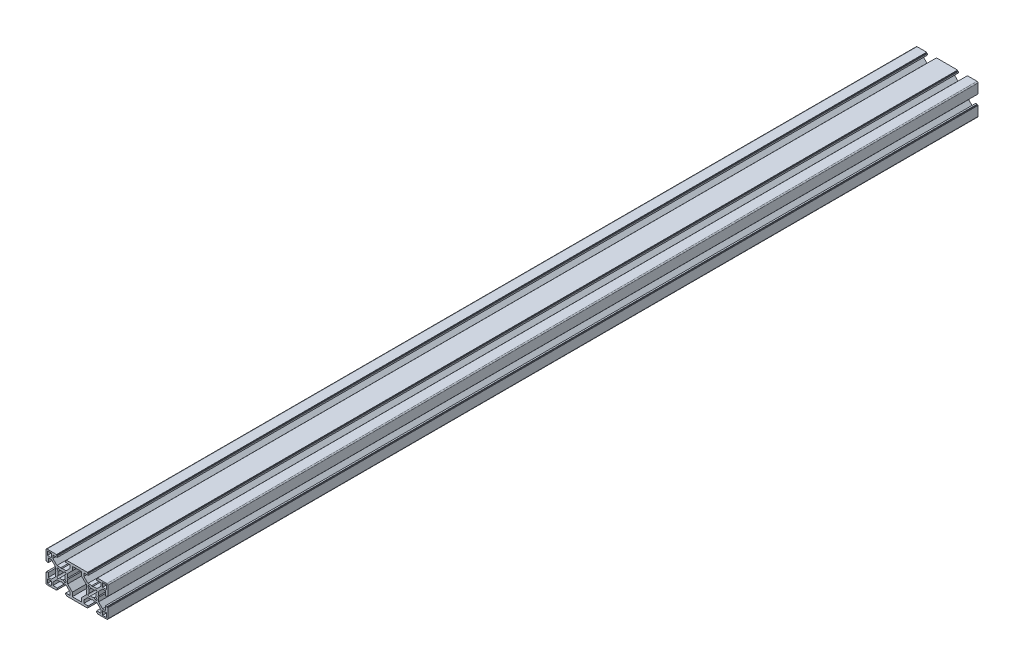
SolidWorks part; units mm, degrees
material "6061 Alloy"
ref_plane "Front Plane" through (0, 0, 0) normal (0, 0, 1) x (1, 0, 0)
ref_plane "Top Plane" through (0, 0, 0) normal (0, 1, 0) x (1, 0, 0)
ref_plane "Right Plane" through (0, 0, 0) normal (1, 0, 0) x (0, 0, -1)
sketch3d "3DSketch1"
  line L0 (0, 0, 0) -> (0, 0, -843)
  dimension "D1" = 843
other "T-slot CNCCAT-3060(1)"
ref_plane "Plane1" through (0, 0, 0) normal (0, 0, -1) x (1, 0, 0)
sketch "Sketch22" plane through (0, 0, 0) normal (0, 0, -1) x (1, 0, 0)
  line L0 (-15, 0) -> (15, 0) construction
  line L1 (30, 15) -> (-30, 15) construction
  line L2 (30, 15) -> (30, -15) construction
  line L3 (24.7696, 13.7304) -> (24.7696, 9.7696)
  line L4 (28.7304, 13.7304) -> (24.7696, 13.7304)
  line L5 (28.7304, 9.7696) -> (28.7304, 13.7304)
  line L6 (24.7696, 9.7696) -> (28.7304, 9.7696)
  line L7 (19.1095, -2.6952) -> (18.0788, -1.6646)
  line L8 (16.6646, -3.0788) -> (17.6952, -4.1095)
  line L9 (-4.492, -12.8) -> (4.492, -12.8)
  line L10 (-4.492, -8.9524) -> (-4.492, -12.8)
  line L11 (-9.0433, -4.4011) -> (-4.492, -8.9524)
  line L12 (-9.0433, -0.6196) -> (-9.0433, -4.4011)
  line L13 (-9.6629, 0) -> (-9.0433, -0.6196)
  line L14 (-9.0433, 0.6196) -> (-9.6629, 0)
  line L15 (-9.0433, 4.4011) -> (-9.0433, 0.6196)
  line L16 (-4.492, 8.9524) -> (-9.0433, 4.4011)
  line L17 (-4.492, 12.8) -> (-4.492, 8.9524)
  line L18 (4.492, 12.8) -> (-4.492, 12.8)
  line L19 (4.492, 8.9524) -> (4.492, 12.8)
  line L20 (9.0433, 4.4011) -> (4.492, 8.9524)
  line L21 (9.0433, 0.6196) -> (9.0433, 4.4011)
  line L22 (9.6629, 0) -> (9.0433, 0.6196)
  line L23 (9.0433, -0.6196) -> (9.6629, 0)
  line L24 (9.0433, -4.4011) -> (9.0433, -0.6196)
  line L25 (4.492, -8.9524) -> (9.0433, -4.4011)
  line L26 (4.492, -12.8) -> (4.492, -8.9524)
  line L27 (12.3048, -4.1095) -> (13.3354, -3.0788)
  line L28 (11.9212, -1.6646) -> (10.8905, -2.6952)
  line L29 (10.8905, 2.6952) -> (11.9212, 1.6646)
  line L30 (13.3354, 3.0788) -> (12.3048, 4.1095)
  line L31 (17.6952, 4.1095) -> (16.6646, 3.0788)
  line L32 (18.0788, 1.6646) -> (19.1095, 2.6952)
  line L33 (28.7304, -13.7304) -> (28.7304, -9.7696)
  line L34 (24.7696, -13.7304) -> (28.7304, -13.7304)
  line L35 (24.7696, -9.7696) -> (24.7696, -13.7304)
  line L36 (28.7304, -9.7696) -> (24.7696, -9.7696)
  line L37 (-28.7304, 13.7304) -> (-28.7304, 9.7696)
  line L38 (-24.7696, 13.7304) -> (-28.7304, 13.7304)
  line L39 (-24.7696, 9.7696) -> (-24.7696, 13.7304)
  line L40 (-28.7304, 9.7696) -> (-24.7696, 9.7696)
  line L41 (-19.1095, 2.6952) -> (-18.0788, 1.6646)
  line L42 (-16.6646, 3.0788) -> (-17.6952, 4.1095)
  line L43 (-12.3048, 4.1095) -> (-13.3354, 3.0788)
  line L44 (-11.9212, 1.6646) -> (-10.8905, 2.6952)
  line L45 (-10.8905, -2.6952) -> (-11.9212, -1.6646)
  line L46 (-13.3354, -3.0788) -> (-12.3048, -4.1095)
  line L47 (-17.6952, -4.1095) -> (-16.6646, -3.0788)
  line L48 (-18.0788, -1.6646) -> (-19.1095, -2.6952)
  line L49 (-24.7696, -13.7304) -> (-24.7696, -9.7696)
  line L50 (-28.7304, -13.7304) -> (-24.7696, -13.7304)
  line L51 (-28.7304, -9.7696) -> (-28.7304, -13.7304)
  line L52 (-24.7696, -9.7696) -> (-28.7304, -9.7696)
  line L53 (30, -15) -> (-30, -15) construction
  line L54 (-30, 15) -> (-30, -15) construction
  line L55 (30, 15) -> (-30, -15) construction
  line L56 (30, -15) -> (-30, 15) construction
  line L57 (-20.3371, 0) -> (-20.9567, -0.6196)
  line L58 (-20.9567, -0.6196) -> (-20.9567, -4.4011)
  line L59 (-20.9567, -4.4011) -> (-24.8637, -8.308)
  line L60 (-24.8637, -8.308) -> (-27.8, -8.308)
  line L61 (-27.8, -8.308) -> (-27.8, -4.1)
  line L62 (-27.8, -4.1) -> (-29.2339, -4.1)
  line L63 (-29.2339, -4.1) -> (-29.2339, -4.7563)
  line L64 (-29.2339, -4.7563) -> (-30, -4.7563)
  line L65 (-30, -4.7563) -> (-30, -14)
  line L66 (-29, -15) -> (-19.7563, -15)
  line L67 (-19.7563, -15) -> (-19.7563, -14.2339)
  line L68 (-19.7563, -14.2339) -> (-19.1, -14.2339)
  line L69 (-19.1, -14.2339) -> (-19.1, -12.8)
  line L70 (-19.1, -12.8) -> (-23.308, -12.8)
  line L71 (-23.308, -12.8) -> (-23.308, -9.8637)
  line L72 (-23.308, -9.8637) -> (-19.4011, -5.9567)
  line L73 (-19.4011, -5.9567) -> (-15.6196, -5.9567)
  line L74 (-15.6196, -5.9567) -> (-15, -5.3371)
  line L75 (-15, -5.3371) -> (-14.3804, -5.9567)
  line L76 (-14.3804, -5.9567) -> (-10.5989, -5.9567)
  line L77 (-10.5989, -5.9567) -> (-6.692, -9.8637)
  line L78 (-6.692, -9.8637) -> (-6.692, -12.8)
  line L79 (-6.692, -12.8) -> (-10.9, -12.8)
  line L80 (-10.9, -12.8) -> (-10.9, -14.2339)
  line L81 (-10.9, -14.2339) -> (-10.2437, -14.2339)
  line L82 (-10.2437, -14.2339) -> (-10.2437, -15)
  line L83 (-10.2437, -15) -> (10.2437, -15)
  line L84 (10.2437, -15) -> (10.2437, -14.2339)
  line L85 (10.2437, -14.2339) -> (10.9, -14.2339)
  line L86 (10.9, -14.2339) -> (10.9, -12.8)
  line L87 (10.9, -12.8) -> (6.692, -12.8)
  line L88 (6.692, -12.8) -> (6.692, -9.8637)
  line L89 (6.692, -9.8637) -> (10.5989, -5.9567)
  line L90 (10.5989, -5.9567) -> (14.3804, -5.9567)
  line L91 (14.3804, -5.9567) -> (15, -5.3371)
  line L92 (15, -5.3371) -> (15.6196, -5.9567)
  line L93 (15.6196, -5.9567) -> (19.4011, -5.9567)
  line L94 (19.4011, -5.9567) -> (23.308, -9.8637)
  line L95 (23.308, -9.8637) -> (23.308, -12.8)
  line L96 (23.308, -12.8) -> (19.1, -12.8)
  line L97 (19.1, -12.8) -> (19.1, -14.2339)
  line L98 (19.1, -14.2339) -> (19.7563, -14.2339)
  line L99 (19.7563, -14.2339) -> (19.7563, -15)
  line L100 (19.7563, -15) -> (29, -15)
  line L101 (30, -14) -> (30, -4.7563)
  line L102 (30, -4.7563) -> (29.2339, -4.7563)
  line L103 (29.2339, -4.7563) -> (29.2339, -4.1)
  line L104 (29.2339, -4.1) -> (27.8, -4.1)
  line L105 (27.8, -4.1) -> (27.8, -8.308)
  line L106 (27.8, -8.308) -> (24.8637, -8.308)
  line L107 (24.8637, -8.308) -> (20.9567, -4.4011)
  line L108 (20.9567, -4.4011) -> (20.9567, -0.6196)
  line L109 (20.9567, -0.6196) -> (20.3371, 0)
  line L110 (20.3371, 0) -> (20.9567, 0.6196)
  line L111 (20.9567, 0.6196) -> (20.9567, 4.4011)
  line L112 (20.9567, 4.4011) -> (24.8637, 8.308)
  line L113 (24.8637, 8.308) -> (27.8, 8.308)
  line L114 (27.8, 8.308) -> (27.8, 4.1)
  line L115 (27.8, 4.1) -> (29.2339, 4.1)
  line L116 (29.2339, 4.1) -> (29.2339, 4.7563)
  line L117 (29.2339, 4.7563) -> (30, 4.7563)
  line L118 (30, 4.7563) -> (30, 14)
  line L119 (29, 15) -> (19.7563, 15)
  line L120 (19.7563, 15) -> (19.7563, 14.2339)
  line L121 (19.7563, 14.2339) -> (19.1, 14.2339)
  line L122 (19.1, 14.2339) -> (19.1, 12.8)
  line L123 (19.1, 12.8) -> (23.308, 12.8)
  line L124 (23.308, 12.8) -> (23.308, 9.8637)
  line L125 (23.308, 9.8637) -> (19.4011, 5.9567)
  line L126 (19.4011, 5.9567) -> (15.6196, 5.9567)
  line L127 (15.6196, 5.9567) -> (15, 5.3371)
  line L128 (15, 5.3371) -> (14.3804, 5.9567)
  line L129 (14.3804, 5.9567) -> (10.5989, 5.9567)
  line L130 (10.5989, 5.9567) -> (6.692, 9.8637)
  line L131 (6.692, 9.8637) -> (6.692, 12.8)
  line L132 (6.692, 12.8) -> (10.9, 12.8)
  line L133 (10.9, 12.8) -> (10.9, 14.2339)
  line L134 (10.9, 14.2339) -> (10.2437, 14.2339)
  line L135 (10.2437, 14.2339) -> (10.2437, 15)
  line L136 (10.2437, 15) -> (-10.2437, 15)
  line L137 (-10.2437, 15) -> (-10.2437, 14.2339)
  line L138 (-10.2437, 14.2339) -> (-10.9, 14.2339)
  line L139 (-10.9, 14.2339) -> (-10.9, 12.8)
  line L140 (-10.9, 12.8) -> (-6.692, 12.8)
  line L141 (-6.692, 12.8) -> (-6.692, 9.8637)
  line L142 (-6.692, 9.8637) -> (-10.5989, 5.9567)
  line L143 (-10.5989, 5.9567) -> (-14.3804, 5.9567)
  line L144 (-14.3804, 5.9567) -> (-15, 5.3371)
  line L145 (-15, 5.3371) -> (-15.6196, 5.9567)
  line L146 (-15.6196, 5.9567) -> (-19.4011, 5.9567)
  line L147 (-19.4011, 5.9567) -> (-23.308, 9.8637)
  line L148 (-23.308, 9.8637) -> (-23.308, 12.8)
  line L149 (-23.308, 12.8) -> (-19.1, 12.8)
  line L150 (-19.1, 12.8) -> (-19.1, 14.2339)
  line L151 (-19.1, 14.2339) -> (-19.7563, 14.2339)
  line L152 (-19.7563, 14.2339) -> (-19.7563, 15)
  line L153 (-19.7563, 15) -> (-29, 15)
  line L154 (-30, 14) -> (-30, 4.7563)
  line L155 (-30, 4.7563) -> (-29.2339, 4.7563)
  line L156 (-29.2339, 4.7563) -> (-29.2339, 4.1)
  line L157 (-29.2339, 4.1) -> (-27.8, 4.1)
  line L158 (-27.8, 4.1) -> (-27.8, 8.308)
  line L159 (-27.8, 8.308) -> (-24.8637, 8.308)
  line L160 (-24.8637, 8.308) -> (-20.9567, 4.4011)
  line L161 (-20.9567, 4.4011) -> (-20.9567, 0.6196)
  line L162 (-20.9567, 0.6196) -> (-20.3371, 0)
  arc A0 (17.6952, -4.1095) -> (19.1095, -2.6952) centre (18.4023, -3.4023) ccw
  arc A1 (13.3354, -3.0788) -> (16.6646, -3.0788) centre (15, 0) ccw
  arc A2 (10.8905, -2.6952) -> (12.3048, -4.1095) centre (11.5977, -3.4023) ccw
  arc A3 (11.9212, 1.6646) -> (11.9212, -1.6646) centre (15, 0) ccw
  arc A4 (12.3048, 4.1095) -> (10.8905, 2.6952) centre (11.5977, 3.4023) ccw
  arc A5 (16.6646, 3.0788) -> (13.3354, 3.0788) centre (15, 0) ccw
  arc A6 (19.1095, 2.6952) -> (17.6952, 4.1095) centre (18.4023, 3.4023) ccw
  arc A7 (18.0788, -1.6646) -> (18.0788, 1.6646) centre (15, 0) ccw
  arc A8 (-17.6952, 4.1095) -> (-19.1095, 2.6952) centre (-18.4023, 3.4023) ccw
  arc A9 (-13.3354, 3.0788) -> (-16.6646, 3.0788) centre (-15, 0) ccw
  arc A10 (-10.8905, 2.6952) -> (-12.3048, 4.1095) centre (-11.5977, 3.4023) ccw
  arc A11 (-11.9212, -1.6646) -> (-11.9212, 1.6646) centre (-15, 0) ccw
  arc A12 (-12.3048, -4.1095) -> (-10.8905, -2.6952) centre (-11.5977, -3.4023) ccw
  arc A13 (-16.6646, -3.0788) -> (-13.3354, -3.0788) centre (-15, 0) ccw
  arc A14 (-19.1095, -2.6952) -> (-17.6952, -4.1095) centre (-18.4023, -3.4023) ccw
  arc A15 (-18.0788, 1.6646) -> (-18.0788, -1.6646) centre (-15, 0) ccw
  arc A16 (-30, -14) -> (-29, -15) centre (-29, -14) ccw
  arc A17 (29, -15) -> (30, -14) centre (29, -14) ccw
  arc A18 (30, 14) -> (29, 15) centre (29, 14) ccw
  arc A19 (-29, 15) -> (-30, 14) centre (-29, 14) ccw
  point P92 (0, 0)
  point P94 (0, 0)
  point P103 (0, 15)
  point P105 (-30, -15)
  point P107 (-30, 15)
  point P109 (0, -15)
  point P111 (30, 0)
  point P113 (30, -15)
  point P115 (30, 15)
  point P117 (-30, 0)
  point P210 (0, 0)
